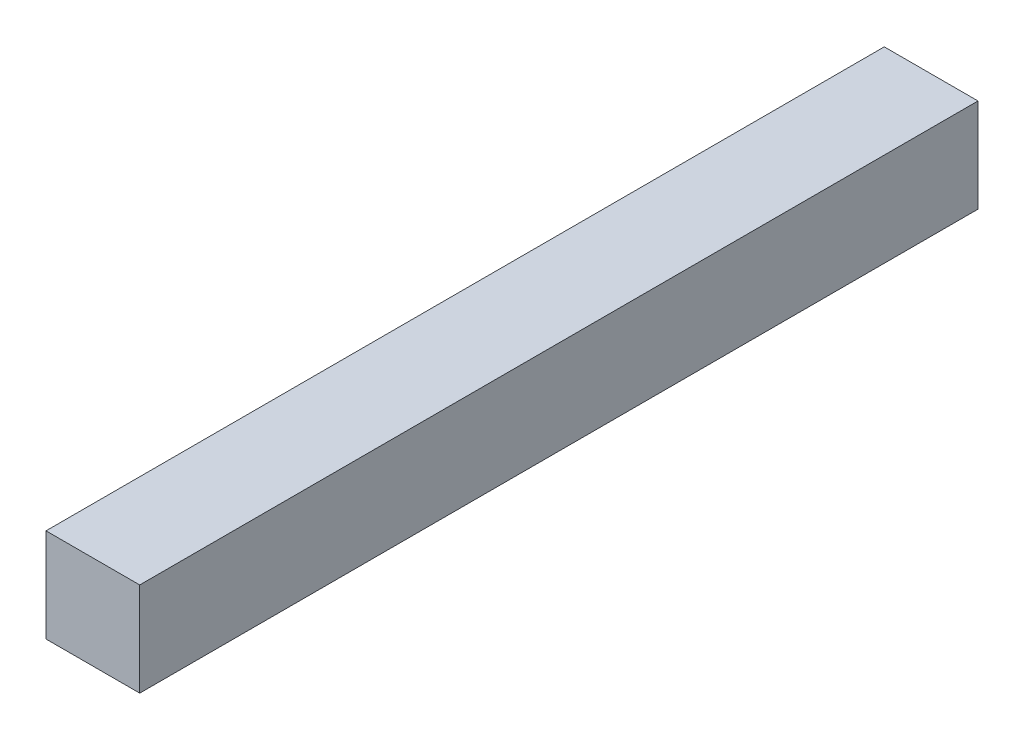
SolidWorks part; units mm, degrees
ref_plane "Front Plane" through (0, 0, 0) normal (0, 0, 1) x (1, 0, 0)
ref_plane "Top Plane" through (0, 0, 0) normal (0, 1, 0) x (1, 0, 0)
ref_plane "Right Plane" through (0, 0, 0) normal (1, 0, 0) x (0, 0, -1)
sketch "Sketch1" plane through (0, 0, 0) normal (0, 0, 1) x (1, 0, 0)
  line L4 (-71, -321) -> (-89, -321)
  line L5 (-89, -321) -> (-89, -339)
  line L6 (-89, -339) -> (-71, -339)
  line L7 (-71, -339) -> (-71, -321)
  line L8 (-71, -321) -> (-89, -321)
  line L9 (-89, -321) -> (-89, -339)
  line L10 (-89, -339) -> (-71, -339)
  line L11 (-71, -339) -> (-71, -321)
  dimension "D1" = 0
extrude "Boss-Extrude1" add sketch "Sketch1" along normal up to vertex (161 mm away)
